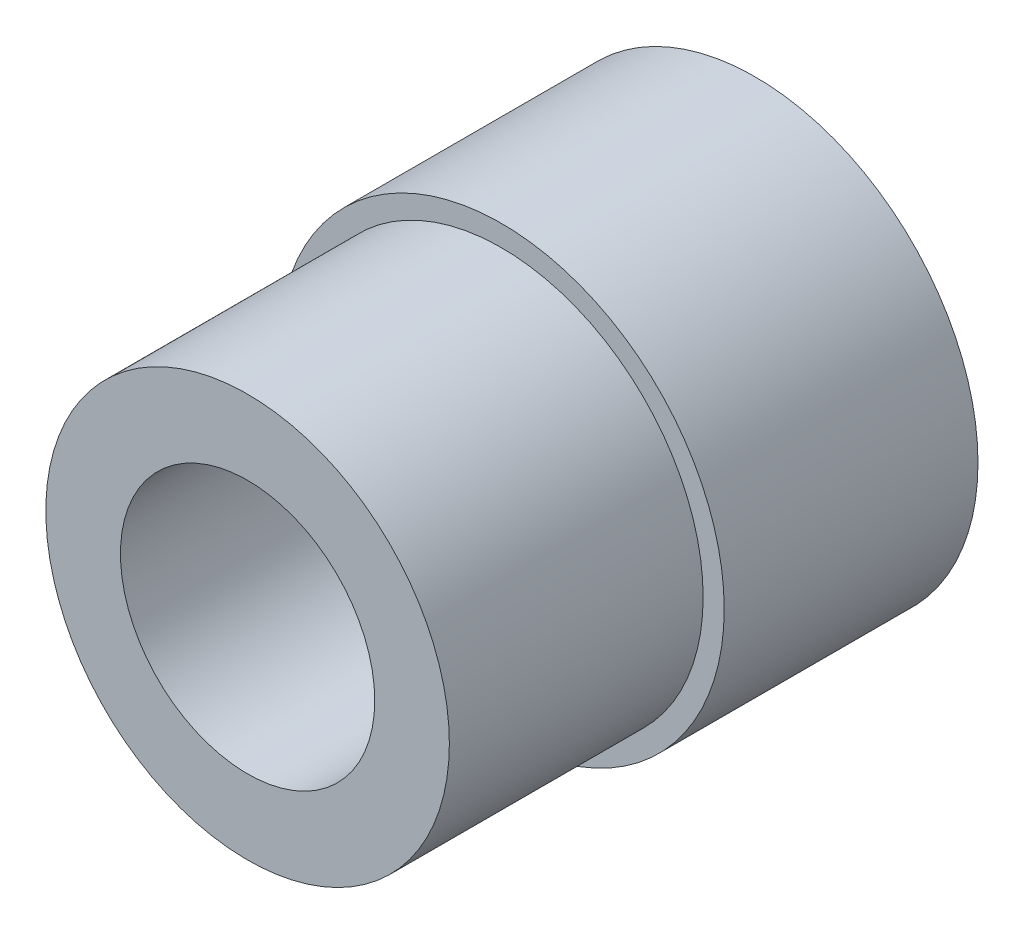
SolidWorks part; units mm, degrees
ref_plane "Front Plane" through (0, 0, 0) normal (0, 0, 1) x (1, 0, 0)
ref_plane "Top Plane" through (0, 0, 0) normal (0, 1, 0) x (1, 0, 0)
ref_plane "Right Plane" through (0, 0, 0) normal (1, 0, 0) x (0, 0, -1)
sketch "Sketch1" plane through (0, 0, 0) normal (0, 0, 1) x (1, 0, 0)
  circle A0 centre (0, 0) radius 11.1506
  circle A1 centre (0, 0) radius 6.3627
  dimension "D1" = 22.3012
  dimension "ID" = 12.7254
extrude "Extrude1" add sketch "Sketch1" along normal mid plane 25.4
sketch "Sketch2" plane through (0, 0, 0) normal (1, 0, 0) x (0, 0, -1)
  line L0 (-12.7, -6.3627) -> (12.7, -6.3627) construction
  line L3 (12.7, 6.3627) -> (-12.7, 6.3627) construction
  line L5 (-12.7, -6.3627) -> (12.7, -6.3627)
  line L6 (12.7, 6.3627) -> (-12.7, 6.3627)
sketch "Sketch4" plane through (0, 0, 12.7) normal (0, 0, 1) x (1, 0, 0)
  line L0 (0, 0) -> (-4.4991, 4.4991)
  line L1 (0, -3.4925) -> (0, 3.4925) construction
  circle A0 centre (0, 0) radius 6.3627 construction
  dimension "D1" = 45
sketch "Sketch5" plane through (0, 0, 12.7) normal (0, 0, 1) x (1, 0, 0)
  circle A0 centre (0, 0) radius 10.0965
  circle M2 centre (0, 0) radius 11.1506
  dimension "D1" = 20.193
extrude "Cut-Extrude1" cut sketch "Sketch5" against normal blind 12.7 contours A0 M2
